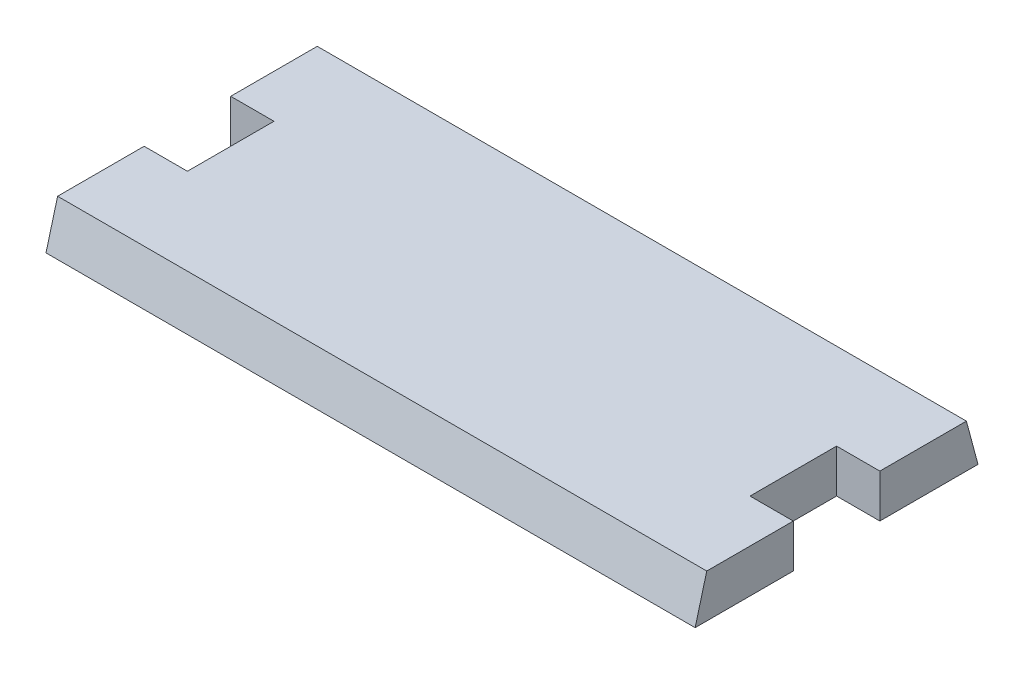
SolidWorks part; units mm, degrees
ref_plane "Front Plane" through (0, 0, 0) normal (0, 0, 1) x (1, 0, 0)
ref_plane "Top Plane" through (0, 0, 0) normal (0, 1, 0) x (1, 0, 0)
ref_plane "Right Plane" through (0, 0, 0) normal (1, 0, 0) x (0, 0, -1)
sketch "Sketch1" plane through (0, 0, 0) normal (0, 1, 0) x (1, 0, 0)
  line L0 (-145.0169, 0) -> (139.7288, 0) construction
  line L1 (-75, 30) -> (75, 30)
  line L2 (-75, 30) -> (-75, 10)
  line L3 (-75, -30) -> (75, -30)
  line L4 (75, 30) -> (75, 10)
  line L5 (-75, 30) -> (75, -30) construction
  line L6 (-75, -30) -> (75, 30) construction
  line L7 (0, -69.4449) -> (0, 83.4474) construction
  line L8 (-75, -10) -> (-65, -10)
  line L9 (75, -10) -> (65, -10)
  line L11 (75, 10) -> (65, 10)
  line L12 (65, -10) -> (65, 10)
  line L17 (-65, -10) -> (-65, 10)
  line L18 (-75, 10) -> (-65, 10)
  line L19 (75, -10) -> (75, -30)
  line L20 (-75, -10) -> (-75, -30)
  point P0 (0, 0)
  dimension "D1" = 60
  dimension "D2" = 150
  dimension "D3" = 10
  dimension "D4" = 20
  dimension "D5" = 10
extrude "Boss-Extrude1" add sketch "Sketch1" along normal blind 10
draft "Draft1" type of draft neutral plane draft angle 15 faces to draft 2 face at (0, 5, 30) face at (0, 5, -30) neutral plane through (0, 10, 0) neutral plane normal (0, 1, 0) parameters "D1"=15
